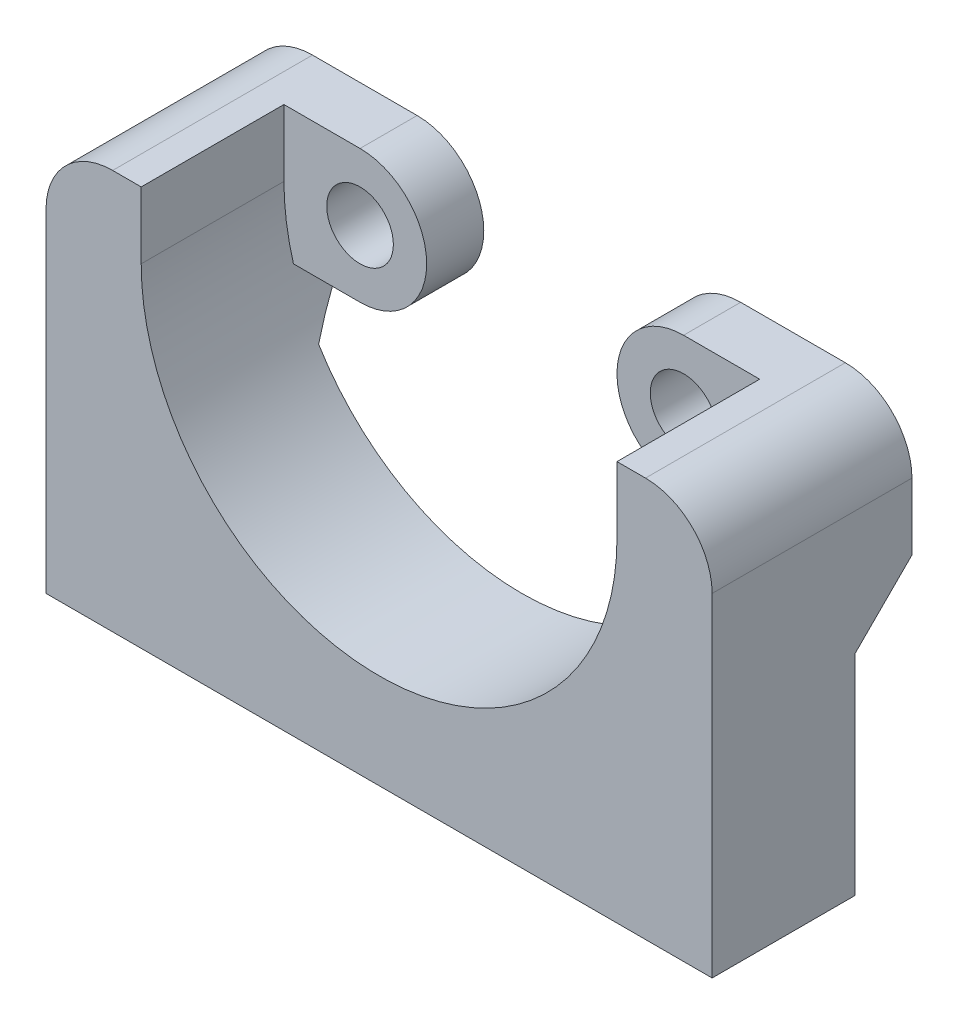
SolidWorks part; units mm, degrees
ref_plane "Front Plane" through (0, 0, 0) normal (0, 0, 1) x (1, 0, 0)
ref_plane "Top Plane" through (0, 0, 0) normal (0, 1, 0) x (1, 0, 0)
ref_plane "Right Plane" through (0, 0, 0) normal (1, 0, 0) x (0, 0, -1)
sketch "Sketch1" plane through (0, 0, 0) normal (0, 0, 1) x (1, 0, 0)
  line L0 (-17.5, 0) -> (17.5, 0)
  line L1 (17.5, 0) -> (17.5, 17.5)
  line L2 (17.5, 17.5) -> (12.5, 17.5)
  line L3 (-17.5, 0) -> (-17.5, 17.5)
  line L4 (-17.5, 17.5) -> (-12.5, 17.5)
  arc A0 (-12.5, 17.5) -> (12.5, 17.5) centre (0, 17.5) ccw
  point P4 (0, 0)
  point P11 (0, 5)
  dimension "D1" = 25
  dimension "D2" = 5
  dimension "D3" = 5
extrude "Boss-Extrude1" add sketch "Sketch1" along normal blind 7.5
sketch "Sketch2" plane through (0, 0, 0) normal (0, 0, -1) x (-1, 0, 0)
  line L0 (-12.5, 17.5) -> (12.5, 17.5) construction
  line L1 (-8.5, 17.5) -> (-14, 17.5) construction
  line L2 (-17.5, 17.5) -> (-12.5, 17.5) construction
  line L3 (-8.5, 14) -> (-14, 14)
  line L4 (-8.5, 21) -> (-14, 21)
  line L5 (0, 4.125) -> (0, -4.125) construction
  line L6 (8.5, 17.5) -> (14, 17.5) construction
  line L7 (8.5, 14) -> (14, 14)
  line L8 (8.5, 21) -> (14, 21)
  circle A0 centre (-8.5, 17.5) radius 1.75
  arc A1 (-8.5, 14) -> (-8.5, 21) centre (-8.5, 17.5) ccw
  arc A2 (-14, 21) -> (-14, 14) centre (-14, 17.5) ccw
  circle A3 centre (8.5, 17.5) radius 1.75
  arc A4 (8.5, 14) -> (8.5, 21) centre (8.5, 17.5) cw
  arc A5 (14, 21) -> (14, 14) centre (14, 17.5) cw
  point P6 (-11.25, 17.5)
  point P14 (-17.5, 17.5)
  point P21 (11.25, 17.5)
  dimension "D1" = 3.5
  dimension "D3" = 3.5
  dimension "D2" = 4
extrude "Boss-Extrude2" add sketch "Sketch2" along normal blind 3
sketch "Sketch3" plane through (0, 17.5, 0) normal (0, 1, 0) x (1, 0, 0)
  line L6 (17.5, 0) -> (12.5, 0)
  line L7 (17.5, 0) -> (17.5, -7.5)
  line L8 (17.5, -7.5) -> (12.5, -7.5)
  line L9 (12.5, 0) -> (12.5, -7.5)
  line L10 (-17.5, 0) -> (-12.5, 0)
  line L11 (-17.5, 0) -> (-17.5, -7.5)
  line L12 (-17.5, -7.5) -> (-12.5, -7.5)
  line L13 (-12.5, 0) -> (-12.5, -7.5)
extrude "Boss-Extrude3" add sketch "Sketch3" along normal up to surface (3.5 mm away) up to face at (-11.25, 21, -1.5)
sketch "Sketch4" plane through (0, 0, 0) normal (0, 0, -1) x (-1, 0, 0)
  line L0 (17.5, 21) -> (17.5, 17.5)
  line L1 (14, 21) -> (17.5, 21)
  arc A0 (14, 14) -> (14, 21) centre (14, 17.5) ccw construction
  arc A1 (17.5, 17.5) -> (14, 21) centre (14, 17.5) ccw
extrude "Cut-Extrude1" cut sketch "Sketch4" against normal through all
sketch "Sketch5" plane through (0, 0, 0) normal (0, 0, -1) x (-1, 0, 0)
  line L0 (14, 14) -> (17.5, 14)
  line L1 (17.5, 17.5) -> (17.5, 0) construction
  line L2 (17.5, 14) -> (17.5, 17.5)
  arc A0 (14, 14) -> (17.5, 17.5) centre (14, 17.5) ccw construction
  arc A1 (14, 14) -> (14, 21) centre (14, 17.5) ccw construction
  arc A2 (17.5, 17.5) -> (14, 14) centre (14, 17.5) cw
extrude "Boss-Extrude4" add sketch "Sketch5" along normal up to surface (3 mm away) up to face at (-11.25, 17.5, -3)
mirror "Mirror1" about plane through (0, 0, 0) normal (1, 0, 0) of "Cut-Extrude1", "Boss-Extrude4"
sketch "Sketch7" plane through (17.5, 0, 0) normal (1, 0, 0) x (0, 0, -1)
  line L0 (3, 14) -> (0, 11)
  line L1 (0, 0) -> (0, 14) construction
  dimension "D1" = 3
rib "Rib1" sketch "Sketch7" sketch "Sketch7" thickness 5.2526 extrusion direction parallel to sketch draft on no parameters "D1"=5.2526
mirror "Mirror2" about plane through (0, 0, 0) normal (1, 0, 0) of "Rib1"
sketch "Sketch8" plane through (-12.2474, 0, 0) normal (1, 0, 0) x (0, 0, -1)
  line L0 (3, 14) -> (0, 11)
  line L1 (0, 11) -> (0, 14)
  line L2 (0, 14) -> (3, 14)
extrude "Boss-Extrude5" add sketch "Sketch8" along normal blind 2
sketch "Sketch9" plane through (0, 0, 0) normal (0, 0, 1) x (1, 0, 0)
  line L0 (-10.2474, 14) -> (-12, 14)
  line L1 (-10.2474, 14) -> (-10.2474, 11)
  line L2 (-10.2474, 11) -> (-10.6771, 11)
  arc A0 (-12.5, 17.5) -> (-10.6771, 11) centre (0, 17.5) ccw construction
  arc A1 (-12, 14) -> (-10.6771, 11) centre (0, 17.5) ccw
extrude "Cut-Extrude2" cut sketch "Sketch9" against normal through all
mirror "Mirror3" about plane through (0, 0, 0) normal (1, 0, 0) of "Boss-Extrude5", "Cut-Extrude2"
